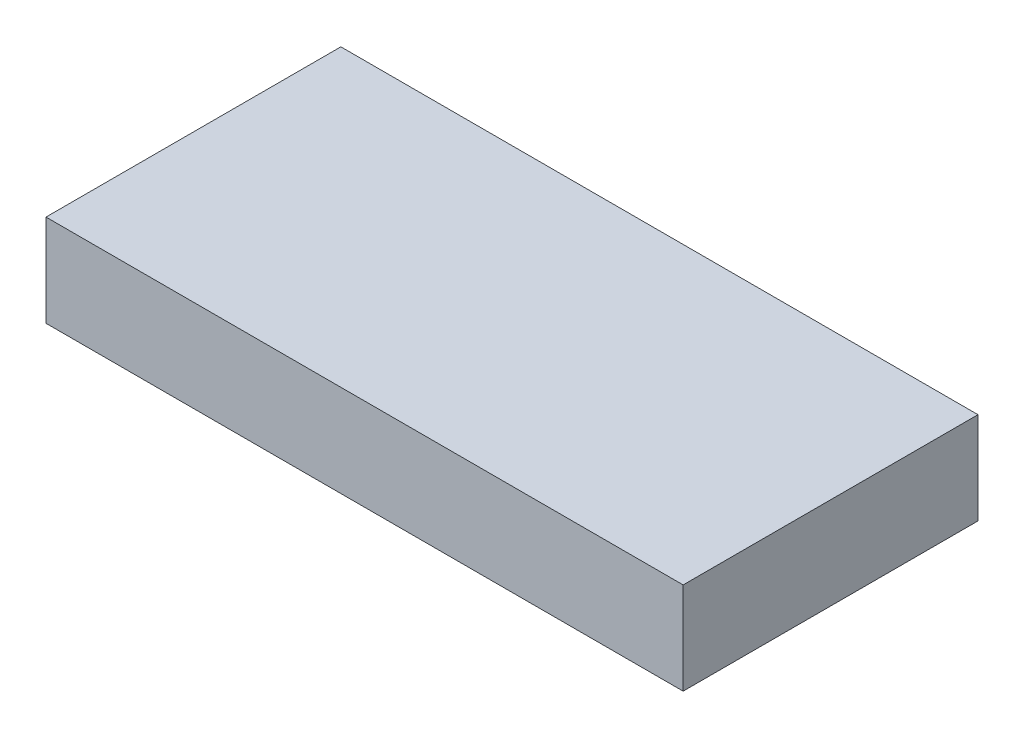
SolidWorks part; units mm, degrees
ref_plane "Front Plane" through (0, 0, 0) normal (0, 0, 1) x (1, 0, 0)
ref_plane "Top Plane" through (0, 0, 0) normal (0, 1, 0) x (1, 0, 0)
ref_plane "Right Plane" through (0, 0, 0) normal (1, 0, 0) x (0, 0, -1)
sketch "Sketch1" plane through (0, 0, 0) normal (0, 1, 0) x (1, 0, 0)
  line L1 (0, 0) -> (1800, 0)
  line L2 (0, 0) -> (0, 833)
  line L3 (0, 833) -> (1800, 833)
  line L4 (1800, 0) -> (1800, 833)
  dimension "D1" = 1800
  dimension "D2" = 833
extrude "Boss-Extrude1" add sketch "Sketch1" along normal blind 260
